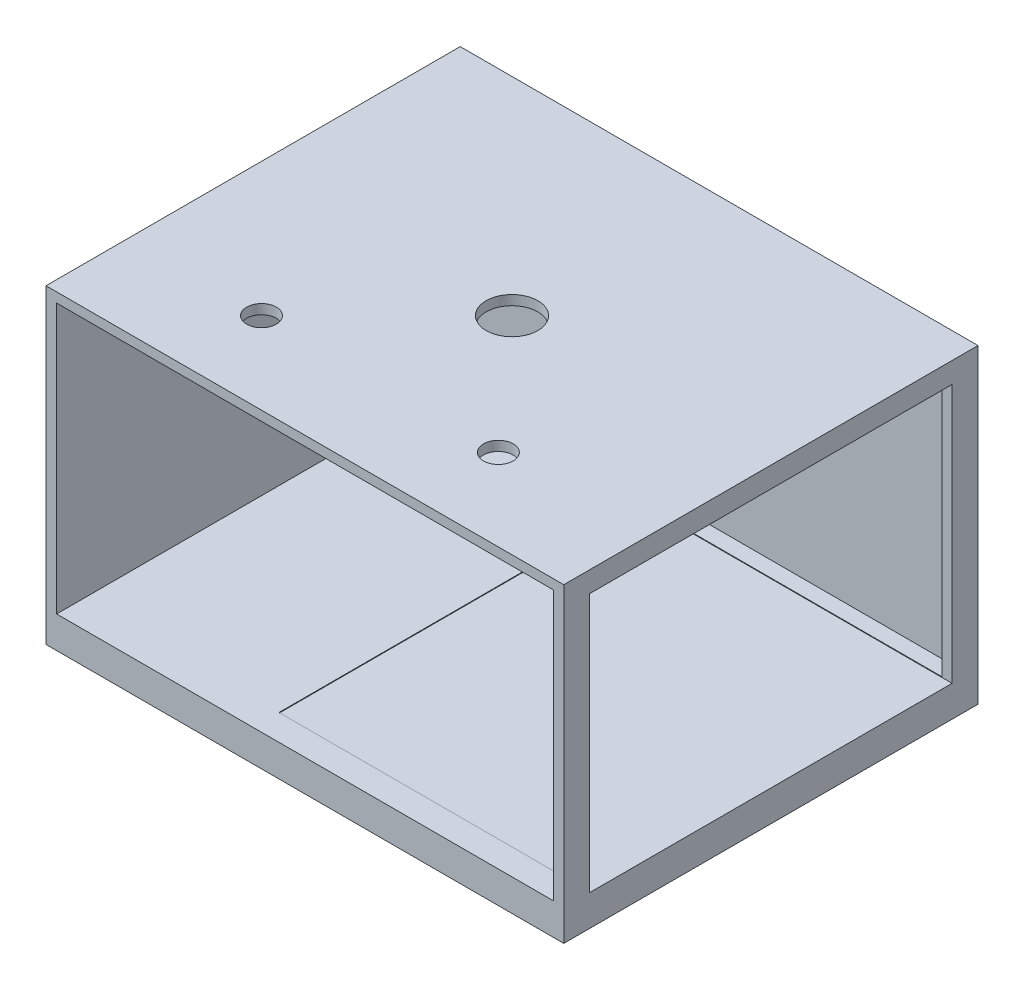
SolidWorks part; units mm, degrees
ref_plane "Front Plane" through (0, 0, 0) normal (0, 0, 1) x (1, 0, 0)
ref_plane "Top Plane" through (0, 0, 0) normal (0, 1, 0) x (1, 0, 0)
ref_plane "Right Plane" through (0, 0, 0) normal (1, 0, 0) x (0, 0, -1)
ref_plane "Plane1" through (250, 0, 0) normal (1, 0, 0) x (0, 0, -1)
sketch "Sketch1" plane through (250, 0, 0) normal (1, 0, 0) x (0, 0, -1)
  line L0 (-200, 290.6321) -> (-200, 280)
  line L1 (-200, 280) -> (175, 280)
  line L2 (175, 280) -> (175, 290.6321)
  line L3 (175, 290.6321) -> (-200, 290.6321)
extrude "Boss-Extrude1" add sketch "Sketch1" against normal blind 9.7389
sketch "Sketch2" plane through (0, 280, 0) normal (0, -1, 0) x (1, 0, 0)
  line L0 (250, 175) -> (240.2611, 175)
  line L1 (240.2611, 175) -> (240.2611, 200)
  line L2 (240.2611, 200) -> (250, 200)
  line L3 (250, 200) -> (250, 175)
extrude "Boss-Extrude2" add sketch "Sketch2" along normal blind 249.3679
sketch "Sketch3" plane through (0, 30.6321, 0) normal (0, -1, 0) x (1, 0, 0)
  line L0 (-50, 175) -> (-50, -175)
  line L1 (-50, -175) -> (-239.7389, -175)
  line L2 (-239.7389, -175) -> (-239.7389, 200)
  line L3 (-239.7389, 200) -> (250, 200)
  line L4 (250, 200) -> (250, 175)
  line L5 (250, 175) -> (-50, 175)
extrude "Boss-Extrude3" add sketch "Sketch3" along normal blind 0.6321
sketch "Sketch4" plane through (0, 30, 0) normal (0, -1, 0) x (1, 0, 0)
  line L0 (-239.7389, -175) -> (-239.7389, 200)
  line L1 (-239.7389, 200) -> (250, 200)
  line L2 (250, 200) -> (250, -175)
  line L3 (250, -175) -> (-239.7389, -175)
extrude "Boss-Extrude4" add sketch "Sketch4" along normal blind 30
sketch "Sketch5" plane through (0, 0, -175) normal (0, 0, -1) x (-1, 0, 0)
  line L0 (239.7389, 0) -> (-250, 0)
  line L1 (-250, 0) -> (-250, 290.6321)
  line L2 (-250, 290.6321) -> (239.7389, 290.6321)
  line L3 (239.7389, 290.6321) -> (239.7389, 0)
extrude "Boss-Extrude5" add sketch "Sketch5" along normal blind 25
sketch "Sketch6" plane through (-239.7389, 0, 0) normal (-1, 0, 0) x (0, 0, 1)
  line L0 (-200, 290.6321) -> (200, 290.6321)
  line L1 (200, 290.6321) -> (200, 0)
  line L2 (200, 0) -> (-200, 0)
  line L3 (-200, 0) -> (-200, 290.6321)
extrude "Boss-Extrude6" add sketch "Sketch6" along normal blind 10.2611
sketch "Sketch7" plane through (0, 290.6321, 0) normal (0, 1, 0) x (-1, 0, 0)
  line L0 (-250, -200) -> (-250, 200)
  line L1 (-250, 200) -> (250, 200)
  line L2 (250, 200) -> (250, -200)
  line L3 (250, -200) -> (-250, -200)
extrude "Boss-Extrude7" add sketch "Sketch7" along normal blind 9.3679
sketch "Sketch8" plane through (0, 0, -175) normal (0, 0, 1) x (1, 0, 0)
  line L0 (240.2611, 30.6321) -> (240.2611, 290.6321)
  line L1 (240.2611, 290.6321) -> (-239.7389, 290.6321)
  line L2 (-239.7389, 290.6321) -> (-239.7389, 30.6321)
  line L3 (-239.7389, 30.6321) -> (240.2611, 30.6321)
extrude "Cut-Extrude1" cut sketch "Sketch8" against normal blind 15
hole_wizard "M25 Clearance Hole1" positions "Sketch10" profile "Sketch9" hole size "M25" standard "ANSI Metric"
sketch "Sketch10" plane through (0, 290.6321, 0) normal (0, -1, 0) x (-1, 0, 0)
  point P0 (-107.7636, -120.9475)
  point P1 (120.9475, -120.9475)
sketch "Sketch9" plane through (107.7636, 290.6321, 120.9475) normal (1, 0, 0) x (0, 0, -1)
  line L0 (0, 0) -> (0, 9.3679)
  line L1 (0, 9.3679) -> (14.3303, 9.3679)
  line L2 (14.3303, 9.3679) -> (14.3303, 0)
  line L5 (14.3303, 0) -> (0, 0)
  line L11 (0, -6.35) -> (0, 107.95) construction
  dimension "Thru Hole Dia." = 28.6605
  dimension "Thru Hole Depth" = 9.3679
hole_wizard "M45 Clearance Hole1" positions "Sketch12" profile "Sketch11" hole size "M45" standard "ANSI Metric"
sketch "Sketch12" plane through (0, 290.6321, 0) normal (0, -1, 0) x (-1, 0, 0)
  point P0 (0, 0)
sketch "Sketch11" plane through (0, 290.6321, 0) normal (1, 0, 0) x (0, 0, -1)
  line L0 (0, 0) -> (0, 9.3679)
  line L1 (0, 9.3679) -> (25, 9.3679)
  line L2 (25, 9.3679) -> (25, 0)
  line L5 (25, 0) -> (0, 0)
  line L11 (0, -6.35) -> (0, 107.95) construction
  dimension "Thru Hole Dia." = 50
  dimension "Thru Hole Depth" = 9.3679
